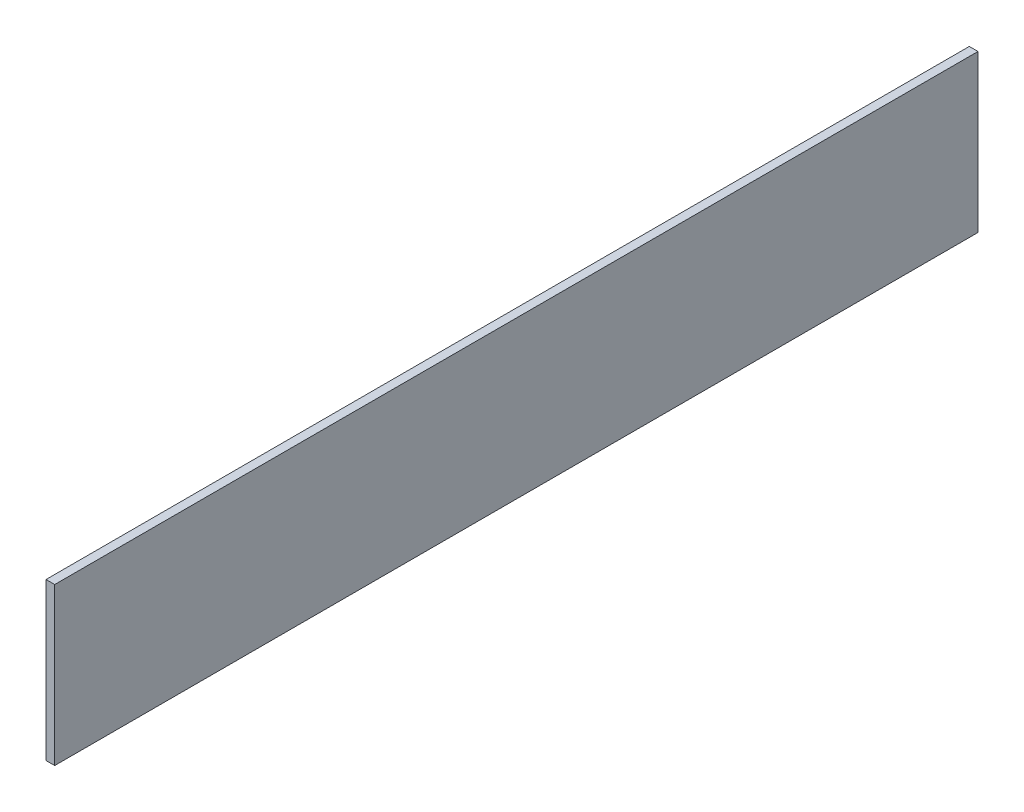
SolidWorks part; units mm, degrees
material "PC High Viscosity"
ref_plane "Front Plane" through (0, 0, 0) normal (0, 0, 1) x (1, 0, 0)
ref_plane "Top Plane" through (0, 0, 0) normal (0, 1, 0) x (1, 0, 0)
ref_plane "Right Plane" through (0, 0, 0) normal (1, 0, 0) x (0, 0, -1)
sketch "Sketch1" plane through (0, 0, 0) normal (1, 0, 0) x (0, 0, -1)
  line L1 (84.1375, 14.2875) -> (-84.1375, 14.2875)
  line L2 (84.1375, 14.2875) -> (84.1375, -14.2875)
  line L3 (84.1375, -14.2875) -> (-84.1375, -14.2875)
  line L4 (-84.1375, 14.2875) -> (-84.1375, -14.2875)
  line L5 (84.1375, 14.2875) -> (-84.1375, -14.2875) construction
  line L6 (84.1375, -14.2875) -> (-84.1375, 14.2875) construction
  point P0 (0, 0)
  dimension "D1" = 28.575
  dimension "D2" = 168.275
extrude "Boss-Extrude1" add sketch "Sketch1" along normal blind 1.5875
